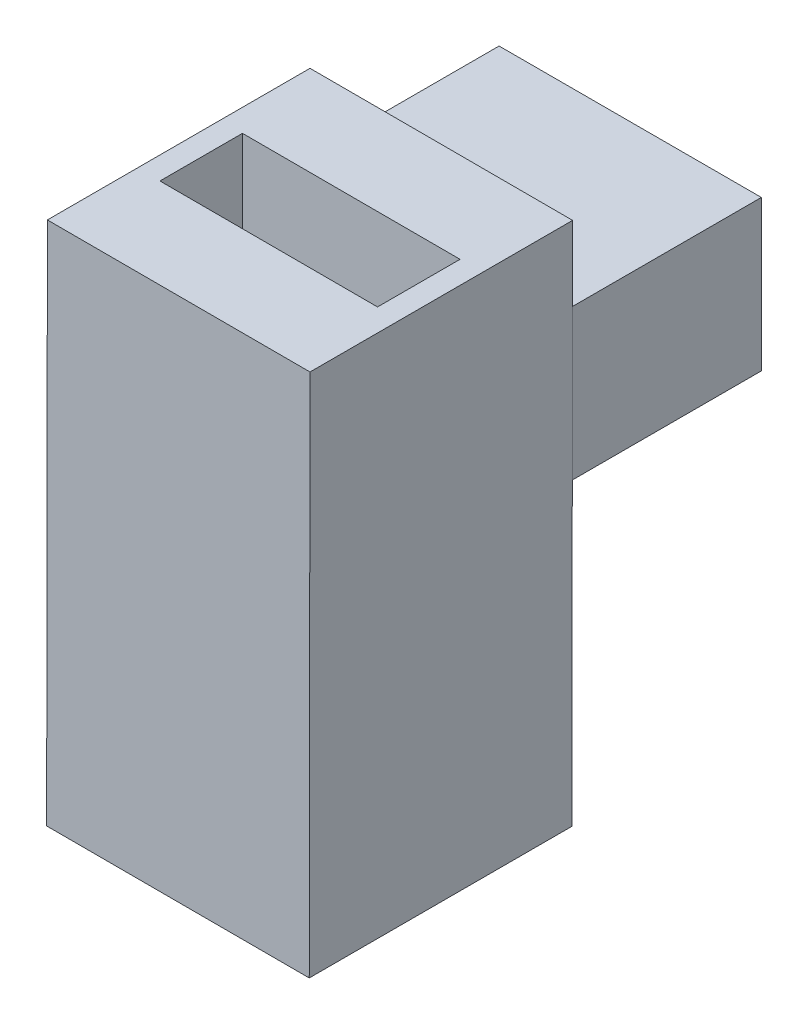
SolidWorks part; units mm, degrees
ref_plane "Front" through (0, 0, 0) normal (0, 0, 1) x (1, 0, 0)
ref_plane "Top" through (0, 0, 0) normal (0, 1, 0) x (1, 0, 0)
ref_plane "Right" through (0, 0, 0) normal (1, 0, 0) x (0, 0, -1)
sketch "Sketch3" plane through (0, 96.8586, 4.3621) normal (-0.0014, -1, 0) x (1, -0.0014, 0)
  line L1 (-8.75, -9.7077) -> (8.75, -9.7077)
  line L2 (-8.75, -9.7077) -> (-8.75, 7.7923)
  line L3 (-8.75, 7.7923) -> (8.75, 7.7923)
  line L4 (8.75, -9.7077) -> (8.75, 7.7923)
  line L5 (-8.75, -9.7077) -> (8.75, 7.7923) construction
  line L6 (-8.75, 7.7923) -> (8.75, -9.7077) construction
  circle A0 centre (0, -0.9577) radius 6.75
  circle A1 centre (0, -0.9577) radius 8.75 construction
  dimension "D1" = 13.5
  dimension "D2" = 2
extrude "Boss-Extrude2" add sketch "Sketch3" along normal blind 20 separate body
sketch "Sketch1" plane through (0, 0, -5.3455) normal (0, 0, 1) x (1, 0, 0)
  line L0 (-2.24, 103.1286) -> (2.24, 103.1286)
  line L2 (-8.7281, 96.8711) -> (8.75, 96.8461)
  line L3 (-8.7281, 96.8711) -> (-8.7281, 106.8586)
  line L4 (-8.7281, 106.8586) -> (8.75, 106.8586)
  line L5 (8.75, 96.8461) -> (8.75, 106.8586)
  line L6 (-8.7281, 96.8711) -> (8.75, 106.8586) construction
  line L7 (-8.7281, 106.8586) -> (8.75, 96.8461) construction
  line L13 (8.75, 96.8461) -> (-8.75, 96.8711) construction
  line L14 (8.75, 96.8461) -> (-8.75, 96.8711) construction
  arc A0 (-2.24, 103.1286) -> (2.24, 103.1286) centre (0, 101.8586) ccw
  circle A2 centre (0, 101.8586) radius 1.5 construction
  arc A3 (2.24, 103.1286) -> (-2.24, 103.1286) centre (0, 101.8586) ccw construction
  circle A4 centre (0, 101.8586) radius 5 construction
  point P10 (0, 0)
  dimension "D1" = 5.15
  dimension "D3" = 10
  dimension "D2" = 4.48
extrude "Boss-Extrude1" add sketch "Sketch1" against normal blind 12.6
sketch "Sketch4" plane through (-0.0693, 96.8587, 0) normal (-0.0014, -1, 0) x (-1, 0.0014, 0)
  line L1 (-7.3193, -6.1545) -> (7.1807, -6.1545)
  line L2 (-7.3193, -6.1545) -> (-7.3193, -0.6545)
  line L3 (-7.3193, -0.6545) -> (7.1807, -0.6545)
  line L4 (7.1807, -6.1545) -> (7.1807, -0.6545)
  line L5 (-7.3193, -6.1545) -> (7.1807, -0.6545) construction
  line L6 (-7.3193, -0.6545) -> (7.1807, -6.1545) construction
  line L10 (-8.8193, 5.3455) -> (-8.8193, -12.1545)
  line L11 (8.6807, 5.3455) -> (-8.8193, 5.3455)
  line L12 (8.6807, -12.1545) -> (8.6807, 5.3455)
  line L13 (-8.8193, -12.1545) -> (8.6807, -12.1545)
  line L14 (6.9307, -0.9045) -> (-7.0693, -0.9045) construction
  line L15 (-7.0693, -0.9045) -> (-7.0693, -5.9045) construction
  line L16 (-7.0693, -5.9045) -> (6.9307, -5.9045) construction
  line L17 (6.9307, -5.9045) -> (6.9307, -0.9045) construction
  line L18 (-8.8193, 5.3455) -> (-8.8193, -12.1545)
  line L19 (8.6807, 5.3455) -> (-8.8193, 5.3455)
  line L20 (8.6807, -12.1545) -> (8.6807, 5.3455)
  line L21 (-8.8193, -12.1545) -> (8.6807, -12.1545)
  circle A2 centre (-0.0693, -3.4045) radius 6.75 construction
  circle A3 centre (-0.0693, -3.4045) radius 6.75 construction
  point P16 (0, 0)
  point P17 (0, 0)
  point P18 (0, 0)
  dimension "D1" = 0.25
  dimension "D2" = 0.25
  dimension "D3" = 0.25
  dimension "D4" = 0.25
  dimension "D5" = 0
extrude "Boss-Extrude3" add sketch "Sketch4" against normal blind 15
sketch "Sketch2" plane through (0, 0, -17.9455) normal (0, 0, -1) x (-1, 0, 0)
  line L0 (-8.75, 106.8586) -> (8.7281, 106.8586) construction
  line L1 (-8.75, 96.8461) -> (-8.75, 106.8586) construction
  circle A0 centre (0, 101.8586) radius 2.575
  dimension "D1" = 5.15
  dimension "D2" = 5
  dimension "D3" = 8.75
extrude "Cut-Extrude1" cut sketch "Sketch2" against normal blind 5
sketch "Sketch5" plane through (0, 0, -17.9455) normal (0, 0, -1) x (-1, 0, 0)
  line L0 (-2.24, 103.1286) -> (2.24, 103.1286) construction
  line L1 (-2.24, 103.1286) -> (2.24, 103.1286)
  line L3 (2.24, 103.1286) -> (-2.24, 103.1286)
  line L4 (2.24, 103.1286) -> (-2.24, 103.1286)
  arc A2 (2.24, 103.1286) -> (-2.24, 103.1286) centre (0, 101.8586) ccw construction
  arc A4 (-2.24, 103.1286) -> (2.24, 103.1286) centre (0, 101.8586) ccw
  arc A5 (-2.24, 103.1286) -> (2.24, 103.1286) centre (0, 101.8586) ccw
  point P0 (0, 0)
  circle M7 centre (0, 101.8586) radius 2.575
  dimension "D1" = 0
extrude "Cut-Extrude2" cut sketch "Sketch5" against normal up to surface (18.6 mm away) contours L1 M7
